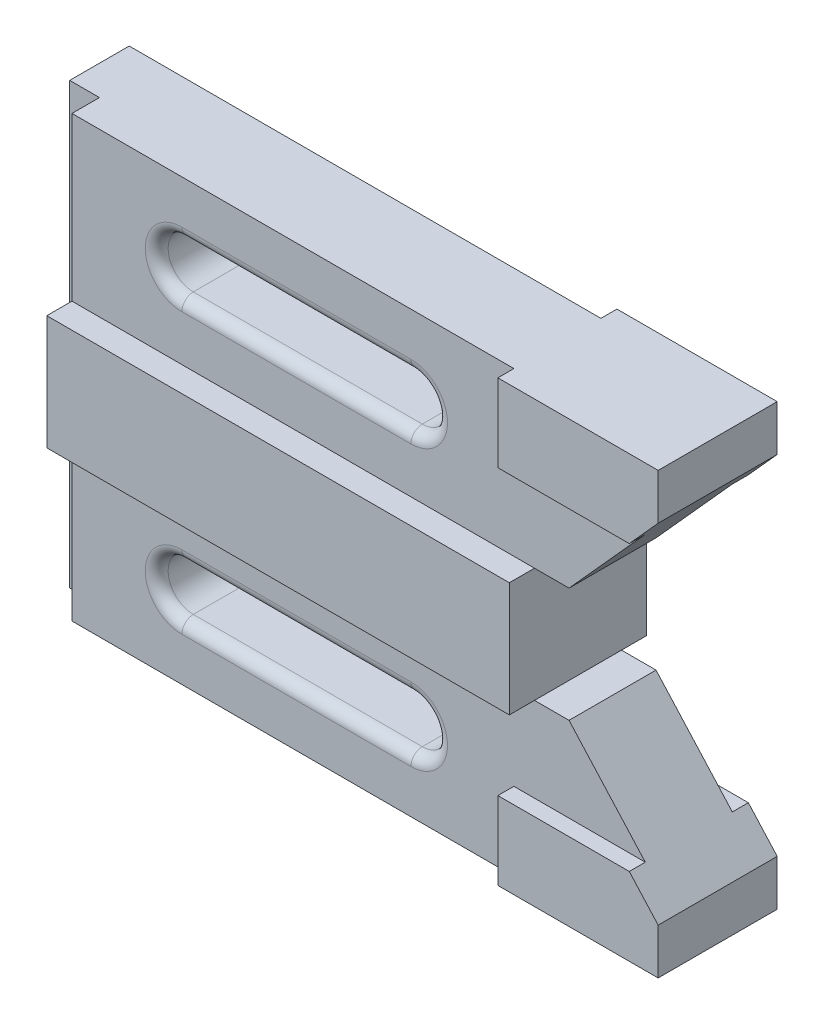
SolidWorks part; units mm, degrees
material "1060 Alloy"
ref_plane "Front Plane" through (0, 0, 0) normal (0, 0, 1) x (1, 0, 0)
ref_plane "Top Plane" through (0, 0, 0) normal (0, 1, 0) x (1, 0, 0)
ref_plane "Right Plane" through (0, 0, 0) normal (1, 0, 0) x (0, 0, -1)
sketch "Sketch1" plane through (0, 0, 0) normal (0, 0, 1) x (1, 0, 0)
  line L0 (0, 0) -> (-138, 0)
  line L1 (-138, 0) -> (-138, 96)
  line L2 (-138, 96) -> (0, 96)
  line L3 (0, 96) -> (0, 86)
  line L5 (-30.5, 60.5) -> (-30.5, 35.5)
  line L6 (-30.5, 35.5) -> (-22.9603, 35.5)
  line L7 (-22.9603, 35.5) -> (0, 10)
  line L8 (0, 10) -> (0, 0)
  line L9 (0, 86) -> (-22.9603, 60.5)
  line L10 (-22.9603, 60.5) -> (-30.5, 60.5)
  line L11 (-107.5, 78.5) -> (-57.5, 78.5) construction
  line L12 (-107.5, 84) -> (-57.5, 84)
  line L13 (-107.5, 73) -> (-57.5, 73)
  line L14 (-107.5, 17.5) -> (-57.5, 17.5) construction
  line L15 (-107.5, 23) -> (-57.5, 23)
  line L16 (-107.5, 12) -> (-57.5, 12)
  arc A0 (-107.5, 84) -> (-107.5, 73) centre (-107.5, 78.5) ccw
  arc A1 (-57.5, 73) -> (-57.5, 84) centre (-57.5, 78.5) ccw
  arc A2 (-107.5, 23) -> (-107.5, 12) centre (-107.5, 17.5) ccw
  arc A3 (-57.5, 12) -> (-57.5, 23) centre (-57.5, 17.5) ccw
  point P12 (-82.5, 78.5)
  point P19 (-82.5, 17.5)
  point P25 (-93.1437, 77.4287)
  point P26 (-93.1437, 23.6227)
  point P27 (0, 0)
  dimension "D12" = 5.5
  dimension "D1" = 138
  dimension "D2" = 96
  dimension "D3" = 10
  dimension "D4" = 48
  dimension "D5" = 35.5
  dimension "D6" = 30.5
  dimension "D7" = 50
  dimension "D8" = 50
  dimension "D9" = 17.5
  dimension "D10" = 30.5
  dimension "D11" = 17.5
extrude "Boss-Extrude1" add sketch "Sketch1" along normal mid plane 19
sketch "Sketch5" plane through (0, 0, 0) normal (0, 0, 1) x (1, 0, 0)
  line L0 (-30.5, 60.5) -> (-138, 60.5)
  line L1 (-138, 96) -> (-138, 0) construction
  line L2 (-30.5, 60.5) -> (-30.5, 35.5)
  line L3 (-30.5, 35.5) -> (-138, 35.5)
  line L4 (-138, 35.5) -> (-138, 60.5)
extrude "Boss-Extrude4" add sketch "Sketch5" along normal mid plane 30
sketch "Sketch6" plane through (0, 0, 0) normal (0, 0, 1) x (1, 0, 0)
  line L0 (-6.3028, 79) -> (-35, 79)
  line L1 (-22.9603, 60.5) -> (0, 86) construction
  line L2 (-35, 79) -> (-35, 96)
  line L3 (0, 96) -> (-138, 96) construction
  line L4 (-35, 96) -> (0, 96)
  line L5 (0, 96) -> (0, 86)
  line L6 (0, 86) -> (-6.3028, 79)
  line L7 (-6.3028, 17) -> (-35, 17)
  line L8 (0, 10) -> (-22.9603, 35.5) construction
  line L9 (-35, 17) -> (-35, 0)
  line L10 (-138, 0) -> (0, 0) construction
  line L11 (-35, 0) -> (0, 0)
  line L12 (0, 0) -> (0, 10)
  line L13 (0, 10) -> (-6.3028, 17)
  dimension "D1" = 17
  dimension "D2" = 35
extrude "Boss-Extrude5" add sketch "Sketch6" along normal mid plane 26
sketch "Sketch7" plane through (0, 96, 0) normal (0, 1, 0) x (1, 0, 0)
  line L0 (-131.5, -15) -> (-131.5, -3.5)
  line L1 (-30.5, -15) -> (-138, -15) construction
  line L2 (-131.5, -3.5) -> (-138, -3.5)
  line L3 (-138, -9.5) -> (-138, 9.5) construction
  line L4 (-138, -3.5) -> (-138, -15)
  line L5 (-138, -15) -> (-131.5, -15)
  dimension "D1" = 11.5
  dimension "D2" = 6.5
extrude "Cut-Extrude1" cut sketch "Sketch7" against normal through all
fillet "Fillet1" radius 2.5 16 edges at (-52, 17.5, -9.5) (-82.5, 12, -9.5) (-113, 17.5, -9.5) (-52, 78.5, -9.5) (-82.5, 73, -9.5) (-113, 78.5, -9.5) (-113, 17.5, 9.5) (-82.5, 23, 9.5) (-52, 17.5, 9.5) (-113, 78.5, 9.5) (-82.5, 84, 9.5) (-52, 78.5, 9.5) (-82.5, 23, -9.5) (-82.5, 84, -9.5) (-82.5, 12, 9.5) (-82.5, 73, 9.5)
equation "\"A\"= 138"
equation "\"B\"= 50"
equation "\"C\"= 48"
equation "\"D1@Sketch1\"=\"A\""
equation "\"D4@Sketch1\"=\"C\""
equation "\"D7@Sketch1\"=\"B\""
equation "\"D8@Sketch1\"=\"B\""
equation "\"D11@Sketch1\"=\"D9@Sketch1\""
